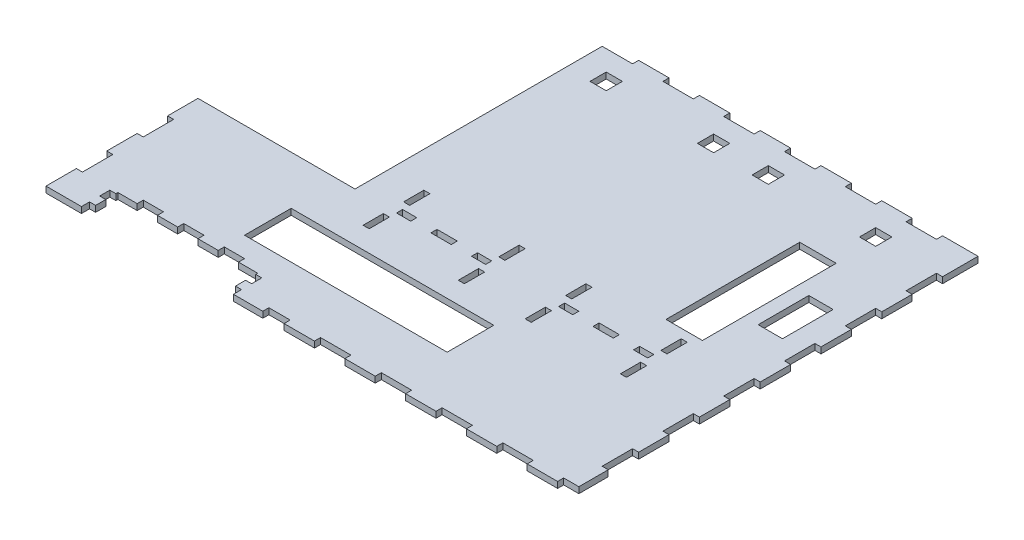
SolidWorks part; units mm, degrees
ref_plane "Alzado" through (0, 0, 0) normal (0, 0, 1) x (1, 0, 0)
ref_plane "Planta" through (0, 0, 0) normal (0, 1, 0) x (1, 0, 0)
ref_plane "Vista lateral" through (0, 0, 0) normal (1, 0, 0) x (0, 0, -1)
sketch "Croquis1" plane through (0, 0, 0) normal (0, 1, 0) x (1, 0, 0)
  line L0 (17.5, 79) -> (20.5, 79)
  line L1 (60, 83) -> (50, 83)
  line L2 (0, 265) -> (17.5, 265) construction
  line L3 (260, 265) -> (260, 247.5)
  line L4 (252.5, 65) -> (237.5, 65)
  line L5 (50, 83) -> (50, 80)
  line L6 (50, 80) -> (40, 80)
  line L7 (40, 80) -> (40, 83)
  line L8 (84.3736, 80) -> (89.5, 80)
  line L9 (40, 83) -> (30, 83)
  line L10 (17.5, 69) -> (20.5, 69)
  line L11 (0, 65) -> (17.5, 65)
  line L12 (92.5, 69) -> (92.5, 65)
  line L13 (20.5, 74) -> (17.5, 74)
  line L14 (92.5, 69) -> (89.5, 69)
  line L15 (30, 83) -> (30, 80)
  line L16 (89.5, 69) -> (89.5, 74)
  line L17 (92.5, 74) -> (92.5, 79)
  line L18 (115, 143) -> (125, 143)
  line L19 (80, 80) -> (84.3736, 80)
  line L20 (89.5, 80) -> (89.5, 79)
  line L21 (30, 80) -> (25.6264, 80)
  line L22 (115, 140) -> (125, 140)
  line L23 (17.5, 69) -> (17.5, 65)
  line L24 (80, 83) -> (80, 80)
  line L25 (89.5, 74) -> (92.5, 74)
  line L26 (70, 83) -> (80, 83)
  line L27 (120, 93) -> (70, 93)
  line L28 (177.5, 65) -> (177.5, 68)
  line L29 (177.5, 68) -> (162.5, 68)
  line L30 (162.5, 68) -> (162.5, 65)
  line L31 (162.5, 65) -> (147.5, 65)
  line L32 (147.5, 65) -> (147.5, 68)
  line L33 (147.5, 68) -> (132.5, 68)
  line L34 (132.5, 68) -> (132.5, 65)
  line L35 (132.5, 65) -> (117.5, 65)
  line L36 (117.5, 65) -> (117.5, 68)
  line L37 (117.5, 68) -> (107, 68)
  line L38 (107, 68) -> (107, 65)
  line L39 (70, 80) -> (70, 83)
  line L40 (92.5, 65) -> (107, 65)
  line L41 (260, 157.5) -> (257, 157.5)
  line L42 (252.5, 68) -> (260, 68)
  line L43 (252.5, 65) -> (252.5, 68)
  line L44 (237.5, 68) -> (237.5, 65)
  line L45 (222.5, 68) -> (237.5, 68)
  line L46 (222.5, 65) -> (222.5, 68)
  line L47 (207.5, 68) -> (207.5, 65)
  line L48 (192.5, 68) -> (207.5, 68)
  line L49 (192.5, 65) -> (192.5, 68)
  line L50 (257, 157.5) -> (257, 142.5)
  line L51 (257, 142.5) -> (260, 142.5)
  line L52 (260, 142.5) -> (260, 127.5)
  line L53 (260, 127.5) -> (257, 127.5)
  line L54 (257, 127.5) -> (257, 112.5)
  line L55 (257, 112.5) -> (260, 112.5)
  line L56 (260, 112.5) -> (260, 97.5)
  line L57 (260, 97.5) -> (257, 97.5)
  line L58 (257, 97.5) -> (257, 82.5)
  line L59 (257, 82.5) -> (260, 82.5)
  line L60 (89.5, 79) -> (92.5, 79)
  line L61 (257, 247.5) -> (260, 247.5)
  line L62 (257, 232.5) -> (257, 247.5)
  line L63 (260, 232.5) -> (257, 232.5)
  line L64 (257, 217.5) -> (260, 217.5)
  line L65 (257, 202.5) -> (257, 217.5)
  line L66 (260, 202.5) -> (257, 202.5)
  line L67 (257, 187.5) -> (260, 187.5)
  line L68 (257, 172.5) -> (257, 187.5)
  line L69 (260, 172.5) -> (257, 172.5)
  line L70 (137.5, 265) -> (137.5, 262)
  line L71 (137.5, 262) -> (152.5, 262)
  line L72 (152.5, 262) -> (152.5, 265)
  line L73 (152.5, 265) -> (167.5, 265)
  line L74 (167.5, 265) -> (167.5, 262)
  line L75 (167.5, 262) -> (182.5, 262)
  line L76 (182.5, 262) -> (182.5, 265)
  line L77 (182.5, 265) -> (197.5, 265)
  line L78 (197.5, 265) -> (197.5, 262)
  line L79 (197.5, 262) -> (212.5, 262)
  line L80 (212.5, 262) -> (212.5, 265)
  line L81 (212.5, 265) -> (227.5, 265)
  line L82 (227.5, 265) -> (227.5, 262)
  line L83 (227.5, 262) -> (242.5, 262)
  line L84 (242.5, 262) -> (242.5, 265)
  line L85 (17.5, 74) -> (17.5, 79)
  line L86 (17.5, 262) -> (17.5, 265) construction
  line L87 (32.5, 262) -> (17.5, 262) construction
  line L88 (32.5, 265) -> (32.5, 262) construction
  line L89 (47.5, 262) -> (47.5, 265) construction
  line L90 (62.5, 262) -> (47.5, 262) construction
  line L91 (62.5, 265) -> (62.5, 262) construction
  line L92 (77.5, 262) -> (77.5, 265) construction
  line L93 (92.5, 262) -> (77.5, 262)
  line L94 (92.5, 265) -> (92.5, 262)
  line L95 (107.5, 262) -> (107.5, 265)
  line L96 (122.5, 262) -> (107.5, 262)
  line L97 (122.5, 265) -> (122.5, 262)
  line L98 (0, 140) -> (3, 140)
  line L99 (3, 140) -> (3, 155) construction
  line L100 (3, 155) -> (0, 155) construction
  line L101 (0, 155) -> (0, 162.5) construction
  line L102 (0, 170) -> (3, 170) construction
  line L103 (3, 170) -> (3, 185) construction
  line L104 (3, 185) -> (0, 185) construction
  line L105 (0, 185) -> (0, 200) construction
  line L106 (0, 200) -> (3, 200) construction
  line L107 (3, 200) -> (3, 215) construction
  line L108 (3, 215) -> (0, 215) construction
  line L109 (0, 215) -> (0, 230) construction
  line L110 (0, 230) -> (3, 230) construction
  line L111 (3, 230) -> (3, 245) construction
  line L112 (3, 245) -> (0, 245) construction
  line L113 (20.5, 69) -> (20.5, 74)
  line L114 (60, 80) -> (70, 80)
  line L115 (60, 83) -> (60, 80)
  line L116 (20.5, 79) -> (20.5, 80)
  line L117 (20.5, 80) -> (25.6264, 80)
  line L118 (70, 93) -> (70, 116)
  line L119 (32.5, 265) -> (47.5, 265) construction
  line L120 (3, 80) -> (0, 80)
  line L121 (3, 95) -> (3, 80)
  line L122 (0, 95) -> (3, 95)
  line L123 (3, 110) -> (0, 110)
  line L124 (3, 125) -> (3, 110)
  line L125 (0, 125) -> (3, 125)
  line L126 (70, 116) -> (170, 116)
  line L127 (170, 116) -> (170, 93)
  line L128 (62.5, 265) -> (77.5, 265) construction
  line L129 (92.5, 265) -> (107.5, 265)
  line L130 (122.5, 265) -> (137.5, 265)
  line L131 (170, 93) -> (120, 93)
  line L132 (195, 143) -> (205, 143)
  line L133 (98, 156.5) -> (98, 146.5)
  line L134 (242.5, 265) -> (260, 265)
  line L135 (0, 245) -> (0, 265) construction
  line L136 (98, 136.5) -> (95, 136.5)
  line L137 (95, 136.5) -> (95, 126.5)
  line L138 (95, 126.5) -> (98, 126.5)
  line L139 (0, 125) -> (0, 140)
  line L140 (0, 95) -> (0, 110)
  line L141 (0, 65) -> (0, 80)
  line L142 (3, 140) -> (77.5, 140)
  line L143 (105, 140) -> (98, 140)
  line L144 (98, 140) -> (98, 143)
  line L145 (98, 143) -> (105, 143)
  line L146 (105, 143) -> (105, 140)
  line L147 (95, 156.5) -> (98, 156.5)
  line L148 (95, 146.5) -> (95, 156.5)
  line L149 (98, 146.5) -> (95, 146.5)
  line L150 (192.5, 65) -> (177.5, 65)
  line L151 (222.5, 65) -> (207.5, 65)
  line L152 (260, 82.5) -> (260, 68)
  line L153 (142, 146.5) -> (145, 146.5)
  line L154 (145, 146.5) -> (145, 156.5)
  line L155 (260, 172.5) -> (260, 157.5)
  line L156 (260, 202.5) -> (260, 187.5)
  line L157 (260, 232.5) -> (260, 217.5)
  line L158 (145, 156.5) -> (142, 156.5)
  line L159 (98, 126.5) -> (98, 136.5)
  line L160 (77.5, 140) -> (77.5, 155)
  line L161 (142, 156.5) -> (142, 146.5)
  line L162 (142, 126.5) -> (142, 136.5)
  line L163 (145, 126.5) -> (142, 126.5)
  line L164 (145, 136.5) -> (145, 126.5)
  line L165 (142, 136.5) -> (145, 136.5)
  line L166 (178, 156.5) -> (178, 146.5)
  line L167 (175, 156.5) -> (178, 156.5)
  line L168 (135, 143) -> (135, 140)
  line L169 (142, 143) -> (135, 143)
  line L170 (142, 140) -> (142, 143)
  line L171 (135, 140) -> (142, 140)
  line L172 (125, 143) -> (125, 140)
  line L173 (115, 140) -> (115, 143)
  line L174 (185, 140) -> (178, 140)
  line L175 (175, 146.5) -> (175, 156.5)
  line L176 (178, 140) -> (178, 143)
  line L177 (178, 146.5) -> (175, 146.5)
  line L178 (222, 146.5) -> (225, 146.5)
  line L179 (225, 146.5) -> (225, 156.5)
  line L180 (222, 140) -> (222, 143)
  line L181 (225, 156.5) -> (222, 156.5)
  line L182 (222, 156.5) -> (222, 146.5)
  line L183 (178, 136.5) -> (175, 136.5)
  line L184 (175, 136.5) -> (175, 126.5)
  line L185 (178, 143) -> (185, 143)
  line L186 (175, 126.5) -> (178, 126.5)
  line L187 (205, 140) -> (205, 143)
  line L188 (185, 143) -> (185, 140)
  line L189 (178, 126.5) -> (178, 136.5)
  line L190 (222, 126.5) -> (222, 136.5)
  line L191 (225, 126.5) -> (222, 126.5)
  line L192 (225, 136.5) -> (225, 126.5)
  line L193 (222, 136.5) -> (225, 136.5)
  line L194 (0, 170) -> (0, 162.5) construction
  line L195 (215, 143) -> (215, 140)
  line L196 (77.5, 155) -> (77.5, 262)
  line L197 (93.5, 248) -> (93.5, 244) construction
  line L198 (89.5, 252) -> (97.5, 252)
  line L199 (215, 140) -> (222, 140)
  line L200 (195, 140) -> (205, 140)
  line L201 (89.5, 252) -> (89.5, 244)
  line L202 (89.5, 244) -> (97.5, 244)
  line L203 (97.5, 252) -> (97.5, 244)
  line L204 (222, 143) -> (215, 143)
  line L205 (195, 140) -> (195, 143)
  line L206 (89.5, 252) -> (97.5, 244) construction
  line L207 (89.5, 244) -> (97.5, 252) construction
  line L208 (146.5, 248) -> (146.5, 244) construction
  line L209 (142.5, 252) -> (150.5, 252)
  line L210 (142.5, 252) -> (142.5, 244)
  line L211 (142.5, 244) -> (150.5, 244)
  line L212 (150.5, 252) -> (150.5, 244)
  line L213 (142.5, 252) -> (150.5, 244) construction
  line L214 (142.5, 244) -> (150.5, 252) construction
  line L215 (173.5, 248) -> (173.5, 244) construction
  line L216 (169.5, 252) -> (177.5, 252)
  line L217 (169.5, 252) -> (169.5, 244)
  line L218 (169.5, 244) -> (177.5, 244)
  line L219 (177.5, 252) -> (177.5, 244)
  line L220 (169.5, 252) -> (177.5, 244) construction
  line L221 (169.5, 244) -> (177.5, 252) construction
  line L222 (226.5, 248) -> (226.5, 244) construction
  line L223 (222.5, 252) -> (230.5, 252)
  line L224 (222.5, 252) -> (222.5, 244)
  line L225 (222.5, 244) -> (230.5, 244)
  line L226 (230.5, 252) -> (230.5, 244)
  line L227 (222.5, 252) -> (230.5, 244) construction
  line L228 (222.5, 244) -> (230.5, 252) construction
  dimension "D6" = 10
  dimension "D14" = 8
  dimension "D16" = 3
  dimension "D70" = 8
  dimension "D7" = 50
  dimension "D8" = 10
  dimension "D9" = 10
  dimension "D10" = 23
  dimension "D11" = 100
  dimension "D12" = 16
  dimension "D13" = 10
  dimension "D15" = 14
  dimension "D17" = 15
  dimension "D18" = 3
  dimension "D19" = 15
  dimension "D20" = 15
  dimension "D21" = 14.5
  dimension "D22" = 15
  dimension "D23" = 74.5
  dimension "D24" = 15
  dimension "D25" = 3
  dimension "D26" = 15
  dimension "D27" = 15
  dimension "D28" = 15
  dimension "D29" = 15
  dimension "D30" = 15
  dimension "D31" = 15
  dimension "D32" = 15
  dimension "D33" = 15
  dimension "D34" = 3
  dimension "D35" = 15
  dimension "D36" = 15
  dimension "D37" = 15
  dimension "D38" = 15
  dimension "D39" = 15
  dimension "D40" = 15
  dimension "D41" = 15
  dimension "D42" = 15
  dimension "D43" = 3
  dimension "D44" = 3
  dimension "D45" = 17.5
  dimension "D46" = 17.5
  dimension "D47" = 15
  dimension "D48" = 3
  dimension "D49" = 15
  dimension "D50" = 15
  dimension "D51" = 15
  dimension "D52" = 3
  dimension "D53" = 15
  dimension "D54" = 15
  dimension "D55" = 15
  dimension "D56" = 15
  dimension "D57" = 15
  dimension "D58" = 3
  dimension "D59" = 17.5
  dimension "D60" = 4
  dimension "D61" = 10
  dimension "D62" = 65
  dimension "D63" = 8
  dimension "D64" = 8
  dimension "D65" = 15
  dimension "D66" = 107
  dimension "D67" = 3
  dimension "D68" = 14
  dimension "D69" = 69
  dimension "D71" = 3
  dimension "D72" = 8
  dimension "D73" = 8
  dimension "D74" = 27
  dimension "D75" = 53
  dimension "D76" = 8
  dimension "D77" = 8
extrude "Saliente-Extruir1" add sketch "Croquis1" along normal blind 3
sketch "Sketch1" plane through (0, 0, 0) normal (0, -1, 0) x (1, 0, 0)
  line L0 (247, -181.5) -> (247, -206.5)
  line L1 (247, -206.5) -> (235, -206.5)
  line L2 (235, -206.5) -> (235, -181.5)
  line L3 (235, -181.5) -> (247, -181.5)
  line L4 (260, -187.5) -> (260, -202.5) construction
  line L6 (210, -161) -> (228, -161)
  line L7 (210, -161) -> (210, -227)
  line L8 (210, -227) -> (228, -227)
  line L9 (228, -161) -> (228, -227)
  line L10 (210, -161) -> (228, -227) construction
  line L11 (210, -227) -> (228, -161) construction
  line L12 (227.5, -265) -> (212.5, -265) construction
  line L13 (219, -194) -> (228, -194) construction
  line L14 (235, -194) -> (247, -194) construction
  point P4 (260, -195)
  point P7 (219, -194)
  dimension "D1" = 13
  dimension "D2" = 25
  dimension "D3" = 12
  dimension "D4" = 7
  dimension "D5" = 18
  dimension "D6" = 66
  dimension "D7" = 38
extrude "Cut-Extrude2" cut sketch "Sketch1" against normal blind 10
